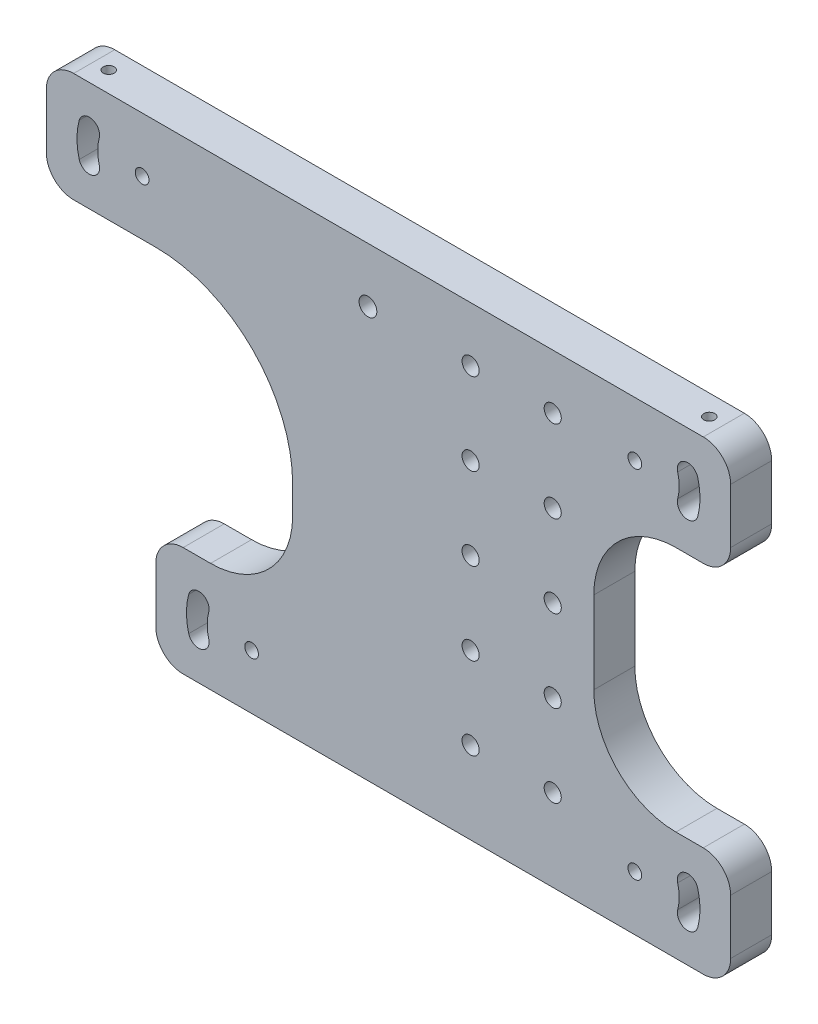
SolidWorks part; units mm, degrees
ref_plane "Front Plane" through (0, 0, 0) normal (0, 0, 1) x (1, 0, 0)
ref_plane "Top Plane" through (0, 0, 0) normal (0, 1, 0) x (1, 0, 0)
ref_plane "Right Plane" through (0, 0, 0) normal (1, 0, 0) x (0, 0, -1)
sketch "Model" plane through (0, 0, 0) normal (0, 0, 1) x (1, 0, 0)
  line L0 (414.2464, 270.8054) -> (426.9464, 270.8054)
  line L1 (376.1464, 194.6054) -> (376.1464, 232.7054)
  line L2 (426.9464, 156.5054) -> (414.2464, 156.5054)
  line L3 (439.6464, 118.4054) -> (439.6464, 143.8054)
  line L4 (185.6464, 105.7054) -> (426.9464, 105.7054)
  line L5 (172.9464, 143.8054) -> (172.9464, 118.4054)
  line L6 (198.3464, 156.5054) -> (185.6464, 156.5054)
  line L7 (236.4464, 207.3054) -> (236.4464, 194.6054)
  line L8 (134.8464, 270.8054) -> (172.9464, 270.8054)
  line L9 (122.1464, 308.9054) -> (122.1464, 283.5054)
  line L10 (426.9464, 321.6054) -> (134.8464, 321.6054)
  line L11 (439.6464, 283.5054) -> (439.6464, 308.9054)
  arc A0 (197.5167, 136.5002) -> (197.5167, 125.7106) centre (217.6504, 131.1054) ccw
  arc A1 (197.5167, 136.5002) -> (188.2243, 138.9901) centre (192.8705, 137.7452) ccw
  arc A2 (188.2243, 138.9901) -> (188.2243, 123.2207) centre (217.6504, 131.1054) ccw
  arc A3 (188.2243, 123.2207) -> (197.5167, 125.7106) centre (192.8705, 124.4657) ccw
  circle A4 centre (357.0964, 143.8054) radius 3.9687
  circle A5 centre (357.0964, 220.0054) radius 3.9687
  arc A6 (424.3685, 123.2207) -> (424.3685, 138.9901) centre (394.9424, 131.1054) ccw
  arc A7 (424.3685, 138.9901) -> (415.076, 136.5002) centre (419.7222, 137.7452) ccw
  arc A8 (415.076, 125.7106) -> (415.076, 136.5002) centre (394.9424, 131.1054) ccw
  arc A9 (415.076, 125.7106) -> (424.3685, 123.2207) centre (419.7222, 124.4657) ccw
  arc A10 (137.4243, 304.0901) -> (137.4243, 288.3207) centre (166.8504, 296.2054) ccw
  arc A11 (137.4243, 288.3207) -> (146.7167, 290.8106) centre (142.0705, 289.5657) ccw
  arc A12 (146.7167, 301.6002) -> (146.7167, 290.8106) centre (166.8504, 296.2054) ccw
  arc A13 (146.7167, 301.6002) -> (137.4243, 304.0901) centre (142.0705, 302.8452) ccw
  circle A14 centre (357.0964, 181.9054) radius 3.9687
  circle A15 centre (395.1964, 296.2054) radius 3.175
  circle A16 centre (357.0964, 258.1054) radius 3.9687
  circle A17 centre (357.0964, 296.2054) radius 3.9687
  circle A18 centre (271.3714, 296.2054) radius 4.1275
  arc A19 (414.2464, 270.8054) -> (376.1464, 232.7054) centre (414.2464, 232.7054) ccw
  arc A20 (376.1464, 194.6054) -> (414.2464, 156.5054) centre (414.2464, 194.6054) ccw
  arc A21 (439.6464, 143.8054) -> (426.9464, 156.5054) centre (426.9464, 143.8054) ccw
  arc A22 (426.9464, 105.7054) -> (439.6464, 118.4054) centre (426.9464, 118.4054) ccw
  arc A23 (172.9464, 118.4054) -> (185.6464, 105.7054) centre (185.6464, 118.4054) ccw
  arc A24 (185.6464, 156.5054) -> (172.9464, 143.8054) centre (185.6464, 143.8054) ccw
  arc A25 (198.3464, 156.5054) -> (236.4464, 194.6054) centre (198.3464, 194.6054) ccw
  arc A26 (236.4464, 207.3054) -> (172.9464, 270.8054) centre (172.9464, 207.3054) ccw
  arc A27 (122.1464, 283.5054) -> (134.8464, 270.8054) centre (134.8464, 283.5054) ccw
  arc A28 (134.8464, 321.6054) -> (122.1464, 308.9054) centre (134.8464, 308.9054) ccw
  arc A29 (439.6464, 308.9054) -> (426.9464, 321.6054) centre (426.9464, 308.9054) ccw
  arc A30 (426.9464, 270.8054) -> (439.6464, 283.5054) centre (426.9464, 283.5054) ccw
  circle A31 centre (318.9964, 296.2054) radius 3.9687
  circle A32 centre (318.9964, 258.1054) radius 3.9687
  circle A33 centre (166.5964, 296.2054) radius 3.175
  circle A34 centre (318.9964, 181.9054) radius 3.9687
  arc A35 (415.076, 290.8106) -> (415.076, 301.6002) centre (394.9424, 296.2054) ccw
  arc A36 (415.076, 290.8106) -> (424.3685, 288.3207) centre (419.7222, 289.5657) ccw
  arc A37 (424.3685, 288.3207) -> (424.3685, 304.0901) centre (394.9424, 296.2054) ccw
  arc A38 (424.3685, 304.0901) -> (415.076, 301.6002) centre (419.7222, 302.8452) ccw
  circle A39 centre (395.1964, 131.1054) radius 3.175
  circle A40 centre (318.9964, 220.0054) radius 3.9687
  circle A41 centre (318.9964, 143.8054) radius 3.9687
  circle A42 centre (217.3964, 131.1054) radius 3.175
extrude "Boss-Extrude1" add sketch "Model" along normal blind 19.05
sketch "Sketch2" plane through (0, 105.7054, 0) normal (0, -1, 0) x (1, 0, 0)
  line L0 (172.9464, 9.525) -> (439.6464, 9.525) construction
  line L1 (172.9464, 19.05) -> (172.9464, 0) construction
  line L2 (439.6464, 19.05) -> (439.6464, 0) construction
  line L3 (306.2964, 19.05) -> (306.2964, 0) construction
  line L4 (185.6464, 19.05) -> (426.9464, 19.05) construction
  line L5 (185.6464, 0) -> (426.9464, 0) construction
  circle A0 centre (192.3774, 9.525) radius 2.5527
  circle A1 centre (420.2154, 9.525) radius 2.5527
  dimension "D1" = 5.1054
  dimension "D2" = 19.431
extrude "Cut-Extrude1" cut sketch "Sketch2" against normal up to next
sketch "Sketch3" plane through (0, 321.6054, 0) normal (0, 1, 0) x (1, 0, 0)
  line L0 (122.1464, -9.525) -> (439.6464, -9.525) construction
  line L1 (122.1464, -19.05) -> (122.1464, 0) construction
  line L2 (439.6464, -19.05) -> (439.6464, 0) construction
  line L3 (280.8964, 0) -> (280.8964, -19.05) construction
  line L4 (426.9464, 0) -> (134.8464, 0) construction
  line L5 (426.9464, -19.05) -> (134.8464, -19.05) construction
  circle A0 centre (141.5774, -9.525) radius 2.5527
  circle A1 centre (420.2154, -9.525) radius 2.5527
  dimension "D1" = 5.1054
  dimension "D2" = 19.431
extrude "Cut-Extrude2" cut sketch "Sketch3" against normal up to next
